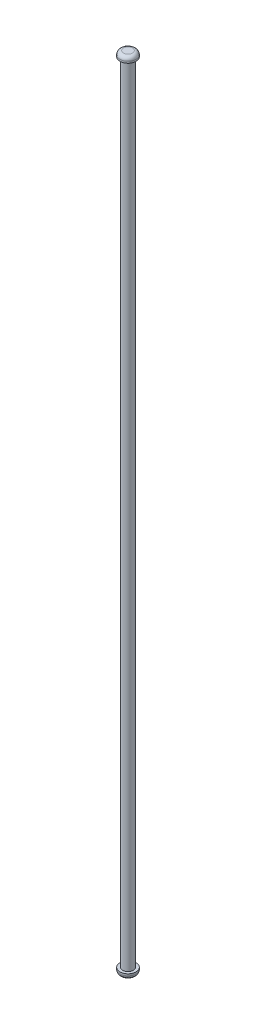
SolidWorks part; units mm, degrees
ref_plane "Front Plane" through (0, 0, 0) normal (0, 0, 1) x (1, 0, 0)
ref_plane "Top Plane" through (0, 0, 0) normal (0, 1, 0) x (1, 0, 0)
ref_plane "Right Plane" through (0, 0, 0) normal (1, 0, 0) x (0, 0, -1)
sketch "Sketch1" plane through (0, 0, 0) normal (0, 1, 0) x (1, 0, 0)
  circle A0 centre (0, 0) radius 1.5
  dimension "D1" = 3
extrude "Boss-Extrude1" add sketch "Sketch1" along normal blind 224
sketch "Sketch2" plane through (0, 224, 0) normal (0, 1, 0) x (1, 0, 0)
  circle A0 centre (0, 0) radius 2.25
  dimension "D1" = 4.5
extrude "Boss-Extrude2" add sketch "Sketch2" against normal blind 1.5
fillet "Fillet1" radius 1 1 edges at (0, 224, 2.25)
sketch "Sketch3" plane through (0, 0, 0) normal (0, -1, 0) x (1, 0, 0)
  circle A0 centre (0, 0) radius 2.25
  dimension "D1" = 4.5
extrude "Boss-Extrude3" add sketch "Sketch3" against normal blind 1.5
fillet "Fillet2" radius 1 1 edges at (0, 0, -2.25)
